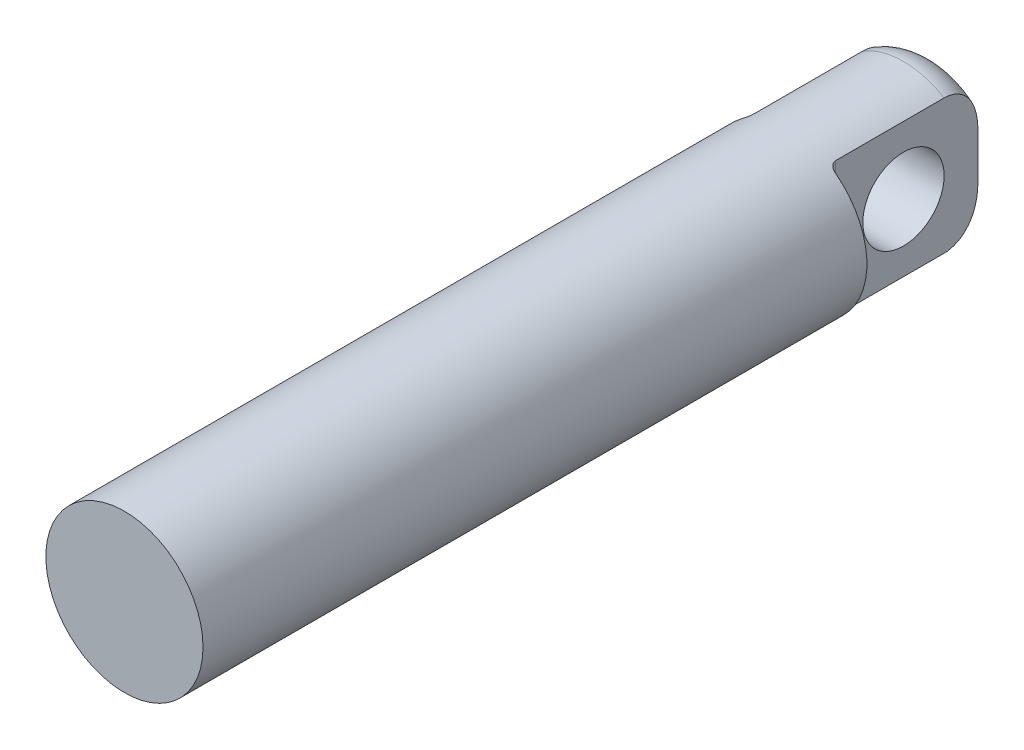
SolidWorks part; units mm, degrees
ref_plane "Front Plane" through (0, 0, 0) normal (0, 0, 1) x (1, 0, 0)
ref_plane "Top Plane" through (0, 0, 0) normal (0, 1, 0) x (1, 0, 0)
ref_plane "Right Plane" through (0, 0, 0) normal (1, 0, 0) x (0, 0, -1)
sketch "Sketch1" plane through (0, 0, 0) normal (0, 0, 1) x (1, 0, 0)
  circle A0 centre (0, 0) radius 2.9
  dimension "D1" = 5.8
extrude "Boss-Extrude1" add sketch "Sketch1" along normal blind 30
sketch "Sketch2" plane through (0, 0, 0) normal (0, 0, -1) x (-1, 0, 0)
  line L1 (-1.5, 2.9) -> (1.5, 2.9)
  line L2 (-1.5, 2.9) -> (-1.5, -2.9)
  line L3 (-1.5, -2.9) -> (1.5, -2.9)
  line L4 (1.5, 2.9) -> (1.5, -2.9)
  line L5 (-1.5, 2.9) -> (1.5, -2.9) construction
  line L6 (-1.5, -2.9) -> (1.5, 2.9) construction
  circle A0 centre (0, 0) radius 2.9 construction
  point P0 (0, 0)
  circle M5 centre (0, 0) radius 2.9
  dimension "D1" = 3
extrude "Cut-Extrude1" cut sketch "Sketch2" against normal blind 5.5 contours L2 M5 | L4 M5
sketch "Sketch3" plane through (-1.5, 0, 0) normal (-1, 0, 0) x (0, 0, 1)
  line L0 (0, 0) -> (5.5, 0) construction
  line L1 (0, 2.4819) -> (0, -2.4819) construction
  line L2 (5.5, 2.4819) -> (5.5, -2.4819) construction
  circle A0 centre (2.75, 0) radius 1.5
  dimension "D1" = 3
extrude "Cut-Extrude2" cut sketch "Sketch3" against normal through all
fillet "Fillet1" radius 1.25 2 edges at (0, 2.9, 0) (0, -2.9, 0)
fillet "Fillet2" radius 0.25 2 edges at (1.5, 0, 5.5) (-1.5, 0, 5.5)
